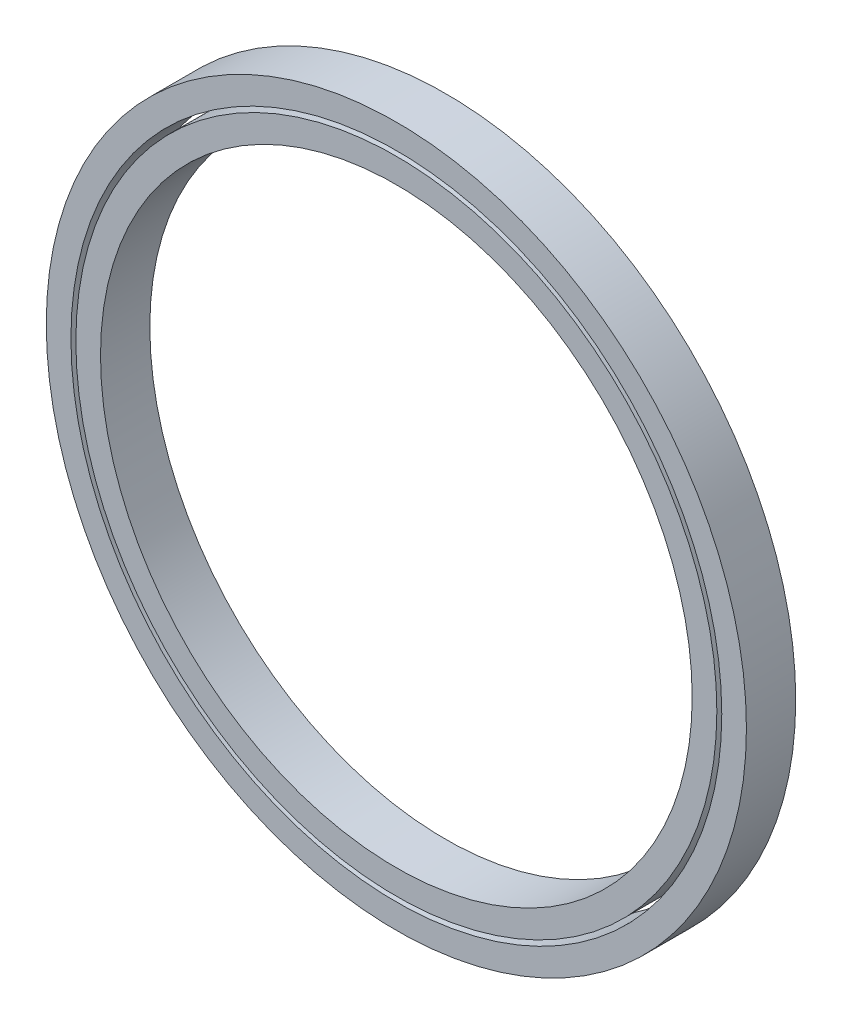
SolidWorks part; units mm, degrees
material "Plain Carbon Steel"
ref_plane "XY" through (0, 0, 0) normal (0, 0, 1) x (1, 0, 0)
ref_plane "XZ" through (0, 0, 0) normal (0, 1, 0) x (1, 0, 0)
ref_plane "YZ" through (0, 0, 0) normal (1, 0, 0) x (0, 0, -1)
sketch "Sketch1" plane through (0, 0, 0) normal (0, 0, 1) x (1, 0, 0)
  line L0 (30, 0) -> (35.5, 0) construction
  line L1 (32.5, 0) -> (33, 0) construction
  circle A0 centre (0, 0) radius 30
  circle A1 centre (0, 0) radius 32.5
  circle A2 centre (0, 0) radius 33
  circle A3 centre (0, 0) radius 35.5
  point P10 (32.75, 0)
  dimension "D1" = 60
  dimension "D2" = 71
  dimension "D3" = 0.5
extrude "Boss-Extrude1" add sketch "Sketch1" along normal mid plane 5 contours A1 A0 | A3 A2
